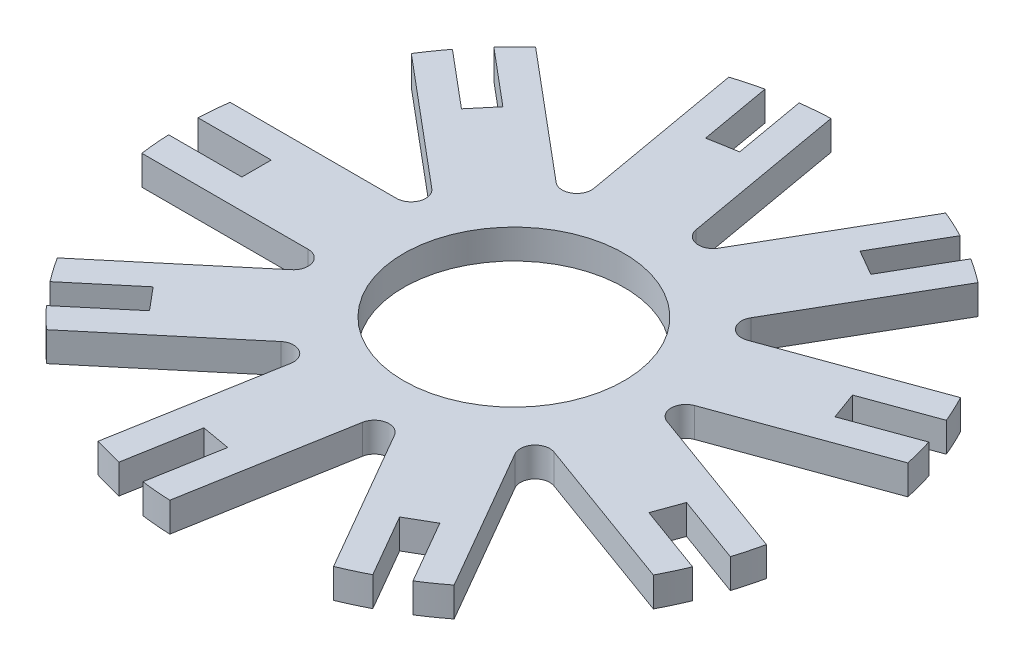
SolidWorks part; units mm, degrees
ref_plane "Front Plane" through (0, 0, 0) normal (0, 0, 1) x (1, 0, 0)
ref_plane "Top Plane" through (0, 0, 0) normal (0, 1, 0) x (1, 0, 0)
ref_plane "Right Plane" through (0, 0, 0) normal (1, 0, 0) x (0, 0, -1)
sketch "Sketch1" plane through (0, 0, 0) normal (0, 1, 0) x (1, 0, 0)
  line L0 (-4.8628, 10.302) -> (-6.8266, 21.4394)
  line L1 (-10.9899, 3) -> (-22.2991, 3)
  line L2 (-10.3471, 4.766) -> (-19.0105, 12.0355)
  line L3 (0, 0) -> (-17.236, 14.4627)
  line L4 (0, 0) -> (-22.5, 0)
  line L5 (-6.4904, 9.3623) -> (-15.1537, 16.6317)
  line L6 (2.8969, 11.0175) -> (8.5515, 20.8116)
  line L7 (1.046, 11.3439) -> (-0.9178, 22.4813)
  line L8 (9.3011, 6.5778) -> (19.9282, 10.4458)
  line L9 (8.093, 8.0175) -> (13.7476, 17.8116)
  line L10 (11.3532, -0.9397) -> (21.9804, -4.8077)
  line L11 (11.3532, 0.9397) -> (21.9804, 4.8077)
  line L12 (8.093, -8.0175) -> (13.7476, -17.8116)
  line L13 (9.3011, -6.5778) -> (19.9282, -10.4458)
  line L14 (1.046, -11.3439) -> (-0.9178, -22.4813)
  line L15 (2.8969, -11.0175) -> (8.5515, -20.8116)
  line L16 (-6.4904, -9.3623) -> (-15.1537, -16.6317)
  line L17 (-4.8628, -10.302) -> (-6.8266, -21.4394)
  line L18 (-10.9899, -3) -> (-22.2991, -3)
  line L19 (-10.3471, -4.766) -> (-19.0105, -12.0355)
  arc A0 (-22.2991, 3) -> (-22.2991, -3) centre (0, 0) ccw
  arc A1 (-10.9899, 3) -> (-10.3471, 4.766) centre (-10.9899, 4) ccw
  arc A2 (-6.4904, 9.3623) -> (-4.8628, 10.302) centre (-5.8476, 10.1284) ccw
  arc A3 (1.046, 11.3439) -> (2.8969, 11.0175) centre (2.0309, 11.5175) ccw
  arc A4 (8.093, 8.0175) -> (9.3011, 6.5778) centre (8.9591, 7.5175) ccw
  arc A5 (11.3532, 0.9397) -> (11.3532, -0.9397) centre (11.6952, 0) ccw
  arc A6 (9.3011, -6.5778) -> (8.093, -8.0175) centre (8.9591, -7.5175) ccw
  arc A7 (2.8969, -11.0175) -> (1.046, -11.3439) centre (2.0309, -11.5175) ccw
  arc A8 (-4.8628, -10.302) -> (-6.4904, -9.3623) centre (-5.8476, -10.1284) ccw
  arc A9 (-10.3471, -4.766) -> (-10.9899, -3) centre (-10.9899, -4) ccw
  circle A10 centre (0, 0) radius 22.5
  circle A11 centre (0, 0) radius 22.5
  arc A12 (-15.1537, 16.6317) -> (-19.0105, 12.0355) centre (0, 0) ccw
  arc A13 (-0.9178, 22.4813) -> (-6.8266, 21.4394) centre (0, 0) ccw
  arc A14 (13.7476, 17.8116) -> (8.5515, 20.8116) centre (0, 0) ccw
  arc A15 (21.9804, 4.8077) -> (19.9282, 10.4458) centre (0, 0) ccw
  arc A16 (19.9282, -10.4458) -> (21.9804, -4.8077) centre (0, 0) ccw
  arc A17 (8.5515, -20.8116) -> (13.7476, -17.8116) centre (0, 0) ccw
  arc A18 (-6.8266, -21.4394) -> (-0.9178, -22.4813) centre (0, 0) ccw
  arc A19 (-19.0105, -12.0355) -> (-15.1537, -16.6317) centre (0, 0) ccw
  dimension "D1" = 45
  dimension "D2" = 9
  dimension "D5" = 2
  dimension "D3" = 3
  dimension "D4" = 40
  dimension "D6" = 3
extrude "Boss-Extrude3" add sketch "Sketch1" along normal blind 2 contours L5 A10 L3 L4 A0 L18 A9 L19 L16 A8 L17 L14 A7 L15 L12 A6 L13 L10 A5 L11 L8 A4 L9 L6 A3 L7 L0 A2 | L3 A10 L2 A1 L1 A0 L4
sketch "Sketch6" plane through (0, 2, 0) normal (0, 1, 0) x (1, 0, 0)
  line L1 (-27.5, -1) -> (-17.5, -1)
  line L2 (-27.5, -1) -> (-27.5, 1)
  line L3 (-27.5, 1) -> (-17.5, 1)
  line L4 (-17.5, -1) -> (-17.5, 1)
  line L5 (-27.5, -1) -> (-17.5, 1) construction
  line L6 (-27.5, 1) -> (-17.5, -1) construction
  arc A0 (-22.2991, 3) -> (-22.2991, -3) centre (0, 0) ccw construction
  point P0 (-22.5, 0)
  dimension "D1" = 10
  dimension "D2" = 2
extrude "Cut-Extrude4" cut sketch "Sketch6" against normal blind 2 contours L2 L1 L4 L3
pattern_circular "CirPattern3" count 9 over 360 about axis through (0, 0, 0) along (0, 1, 0) of "Cut-Extrude4"
sketch "Sketch7" plane through (0, 2, 0) normal (0, 1, 0) x (1, 0, 0)
  circle A0 centre (0, 0) radius 7.5
  dimension "D1" = 15
extrude "Cut-Extrude5" cut sketch "Sketch7" against normal blind 2
